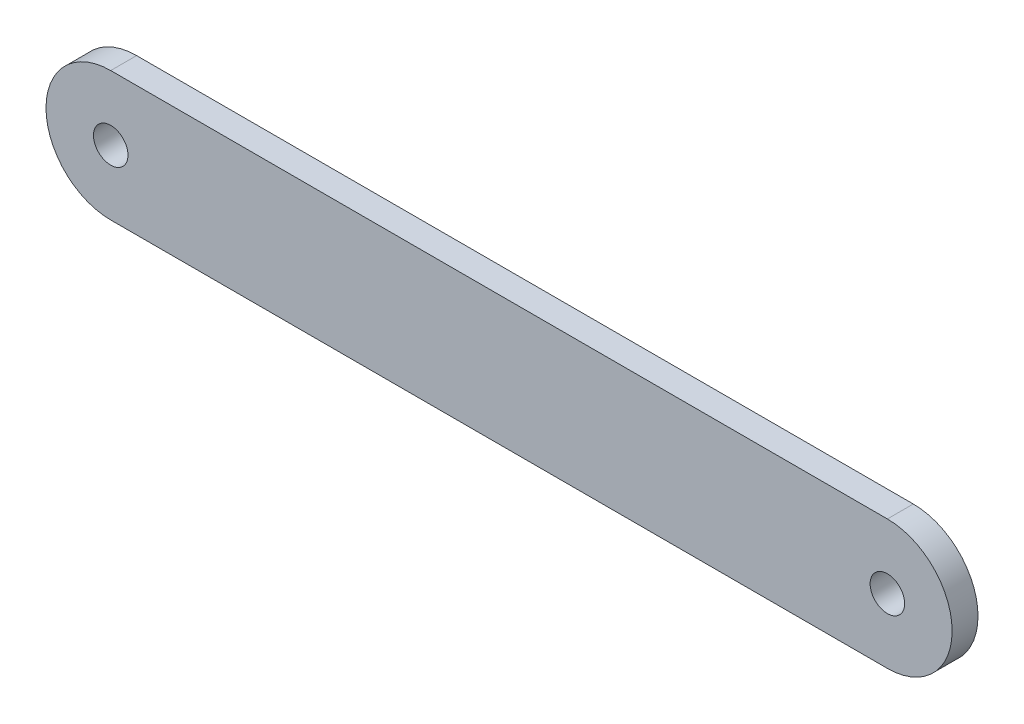
SolidWorks part; units mm, degrees
ref_plane "Front Plane" through (0, 0, 0) normal (0, 0, 1) x (1, 0, 0)
ref_plane "Top Plane" through (0, 0, 0) normal (0, 1, 0) x (1, 0, 0)
ref_plane "Right Plane" through (0, 0, 0) normal (1, 0, 0) x (0, 0, -1)
sketch "Sketch1" plane through (0, 0, 0) normal (0, 0, 1) x (1, 0, 0)
  line L0 (0, 0) -> (90, 0) construction
  line L1 (0, 7.5) -> (90, 7.5)
  line L2 (0, -7.5) -> (90, -7.5)
  arc A0 (0, 7.5) -> (0, -7.5) centre (0, 0) ccw
  arc A1 (90, -7.5) -> (90, 7.5) centre (90, 0) ccw
  circle A2 centre (0, 0) radius 2
  circle A3 centre (90, 0) radius 2
  point P3 (45, 0)
  dimension "D1" = 7.5
  dimension "D3" = 4
  dimension "D4" = 4
  dimension "D2" = 90
extrude "Boss-Extrude1" add sketch "Sketch1" along normal blind 3
